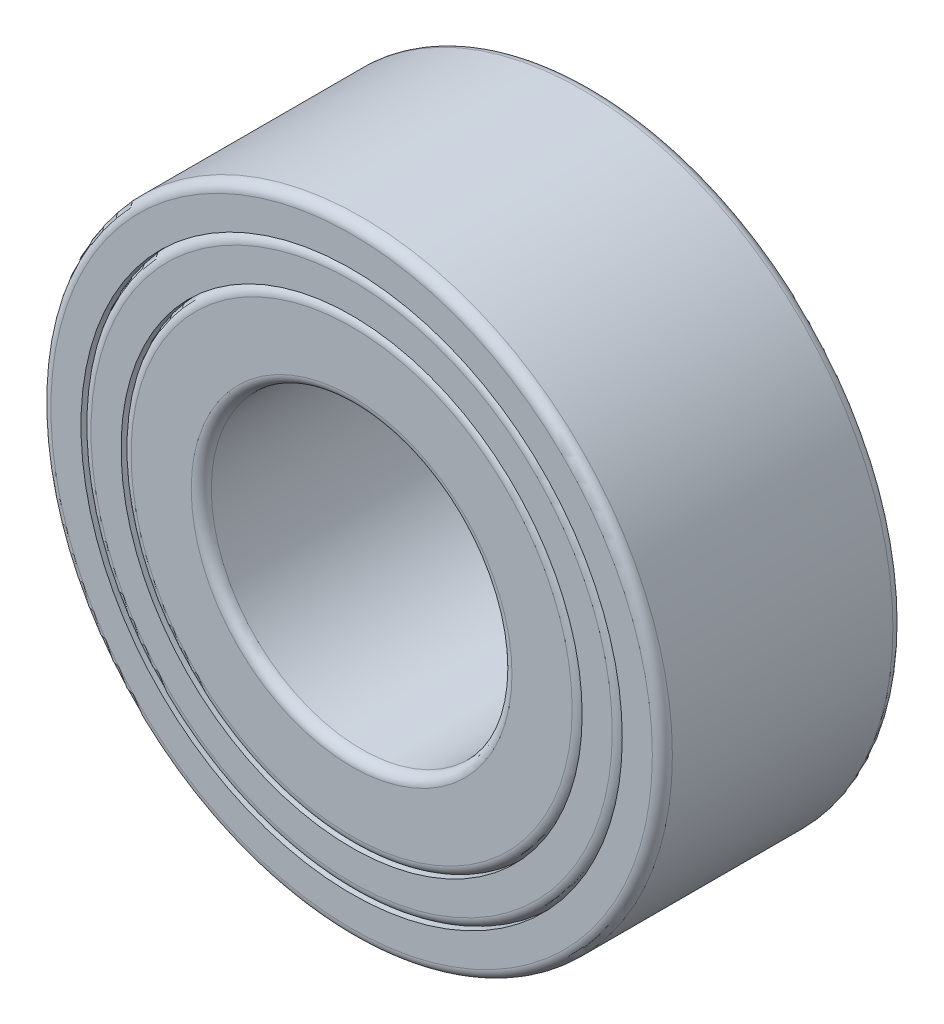
SolidWorks part; units mm, degrees
ref_plane "Front" through (0, 0, 0) normal (0, 0, 1) x (1, 0, 0)
ref_plane "Top" through (0, 0, 0) normal (0, 1, 0) x (1, 0, 0)
ref_plane "Right" through (0, 0, 0) normal (1, 0, 0) x (0, 0, -1)
sketch "Sketch1" plane through (0, 0, 0) normal (0, 0, 1) x (1, 0, 0)
  circle A0 centre (0, 0) radius 15
  circle A1 centre (0, 0) radius 23
extrude "Boss-Extrude1" add sketch "Sketch1" along normal blind 24
fillet "Fillet1" radius 1 2 edges at (23, 0, 0) (23, 0, 24)
sketch "Sketch2" plane through (0, 0, 0) normal (0, 0, 1) x (1, 0, 0)
  circle A0 centre (0, 0) radius 23
  circle A1 centre (0, 0) radius 27
extrude "Boss-Extrude2" add sketch "Sketch2" along normal blind 24
fillet "Fillet2" radius 1 2 edges at (27, 0, 24) (27, 0, 0)
sketch "Sketch3" plane through (0, 0, 0) normal (0, 0, 1) x (1, 0, 0)
  circle A0 centre (0, 0) radius 27
  circle A1 centre (0, 0) radius 31
extrude "Boss-Extrude3" add sketch "Sketch3" along normal blind 24
fillet "Fillet3" radius 1 2 edges at (31, 0, 0) (31, 0, 24)
fillet "Fillet4" radius 1 2 edges at (15, 0, 24) (15, 0, 0)
